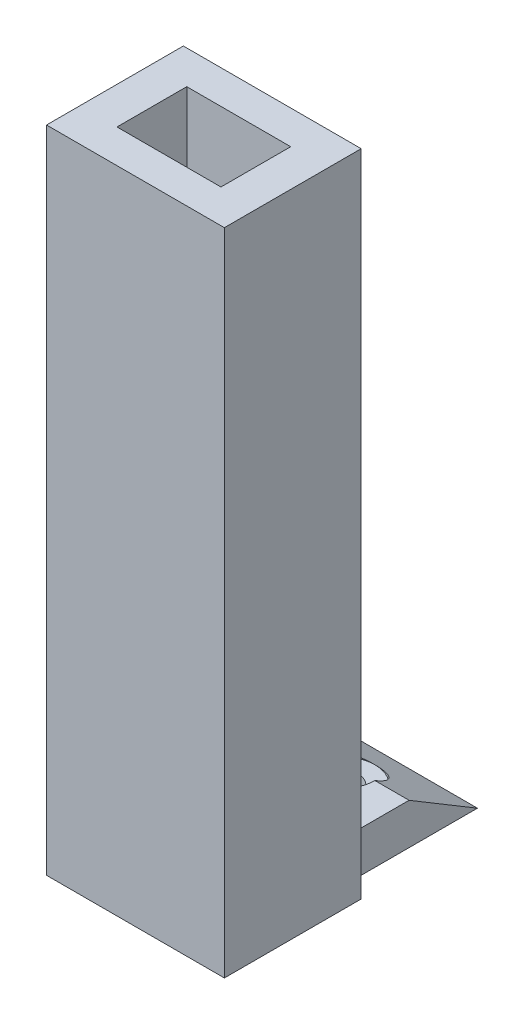
SolidWorks part; units mm, degrees
ref_plane "前视基准面" through (0, 0, 0) normal (0, 0, 1) x (1, 0, 0)
ref_plane "上视基准面" through (0, 0, 0) normal (0, 1, 0) x (1, 0, 0)
ref_plane "右视基准面" through (0, 0, 0) normal (1, 0, 0) x (0, 0, -1)
other "Configuration Table"
sketch "草图1" plane through (0, 0, 0) normal (0, 1, 0) x (1, 0, 0)
  line L5 (-10, -10) -> (10, -10)
  line L7 (-10, 10) -> (10, 10)
  line L9 (10, 10) -> (13, 10)
  line L11 (10, -10) -> (13, -10)
  line L12 (13, 10) -> (13, -10)
  line L13 (-10, 10) -> (-13, 10)
  line L15 (-10, -10) -> (-13, -10)
  line L16 (-13, 10) -> (-13, -10)
extrude "凸台-拉伸1" add sketch "草图1" along normal blind 6 contours L7 L9 L12 L11 L5 L15 L16 L13
sketch "草图2" plane through (0, 6, 0) normal (0, 1, 0) x (1, 0, 0)
  circle A0 centre (0, 0) radius 2.6
extrude "切除-拉伸1" cut sketch "草图2" against normal blind 6
sketch "草图3" plane through (0, 6, 0) normal (0, 1, 0) x (1, 0, 0)
  circle A0 centre (0, 0) radius 5
extrude "切除-拉伸2" cut sketch "草图3" against normal blind 3
sketch "草图4" plane through (0, 6, 0) normal (0, 1, 0) x (1, 0, 0)
  line L1 (-13, 10) -> (13, 10)
  line L2 (-13, 10) -> (-13, -10)
  line L3 (-13, -10) -> (13, -10)
  line L4 (13, 10) -> (13, -10)
  line L5 (-7.5, 5) -> (7.5, 5)
  line L6 (-7.5, 5) -> (-7.5, -5)
  line L7 (-7.5, -5) -> (7.5, -5)
  line L8 (7.5, 5) -> (7.5, -5)
extrude "凸台-拉伸2" add sketch "草图4" along normal blind 89 contours L2 L1 L4 L3 | L6 L5 L8 L7
sketch "草图5" plane through (0, 0, -10) normal (0, 0, -1) x (-1, 0, 0)
  line L0 (0, 0) -> (0, 6)
  line L3 (-7.5, 30) -> (-7.5, 50)
  line L9 (-7.5, 15) -> (-7.5, 30)
  line L11 (7.5, 15) -> (7.5, 30)
  line L12 (-7.5, 50) -> (7.5, 50)
  line L13 (7.5, 30) -> (7.5, 50)
  line L14 (13, 0) -> (-13, 0) construction
  line L16 (0, 6) -> (-7.5, 6)
  line L19 (-7.5, 6) -> (-7.5, 15)
  line L20 (0, 6) -> (7.5, 6)
  line L23 (7.5, 6) -> (7.5, 15)
extrude "切除-拉伸5" cut sketch "草图5" against normal blind 5 contours L20 L23 L11 L13 L12 L3 L9 L19 L16
sketch "草图6" plane through (0, 0, -10) normal (0, 0, -1) x (-1, 0, 0)
  line L0 (7.5, 6) -> (0, 6) construction
  line L1 (7.5, 50) -> (6.5, 50)
  line L2 (7.5, 50) -> (7.5, 6)
  line L3 (7.5, 6) -> (6.5, 6)
  line L4 (6.5, 50) -> (6.5, 6)
  line L5 (-7.5, 6) -> (7.5, 6) construction
  line L6 (-7.5, 50) -> (-6.5, 50)
  line L7 (-7.5, 50) -> (-7.5, 6)
  line L8 (-7.5, 6) -> (-6.5, 6)
  line L9 (-6.5, 50) -> (-6.5, 6)
extrude "凸台-拉伸3" add sketch "草图6" against normal blind 15
sketch "草图8" plane through (0, 0, 0) normal (0, -1, 0) x (1, 0, 0)
  line L1 (-13, -10) -> (13, -10)
  line L2 (-13, -10) -> (-13, -30)
  line L3 (-13, -30) -> (13, -30)
  line L4 (13, -10) -> (13, -30)
  circle A0 centre (0, -20) radius 2.6
extrude "凸台-拉伸4" add sketch "草图8" against normal blind 6
sketch "草图9" plane through (0, 6, 0) normal (0, 1, 0) x (1, 0, 0)
  circle A0 centre (0, 20) radius 5
extrude "切除-拉伸6" cut sketch "草图9" against normal blind 3
sketch "草图10" plane through (-13, 0, 0) normal (-1, 0, 0) x (0, 0, 1)
  line L0 (-20, 6) -> (-30, 0)
  line L1 (-10, 6) -> (-30, 6) construction
  line L2 (-30, 0) -> (-30, 6)
  line L3 (-30, 6) -> (-20, 6)
extrude "切除-拉伸7" cut sketch "草图10" against normal blind 30 contours L3 L0 L2
sketch "草图11" plane through (0, 0, -10) normal (0, 0, -1) x (-1, 0, 0)
  line L0 (13, 0) -> (-13, 0) construction
  line L1 (-13, 6) -> (-10, 6)
  line L2 (-13, 6) -> (-13, 0)
  line L3 (-13, 0) -> (-10, 0)
  line L4 (-10, 6) -> (-10, 0)
  line L6 (13, 6) -> (10, 6)
  line L7 (13, 6) -> (13, 0)
  line L8 (13, 0) -> (10, 0)
  line L9 (10, 6) -> (10, 0)
extrude "切除-拉伸8" cut sketch "草图11" along normal blind 30
sketch "草图12" plane through (0, 95, 0) normal (0, 1, 0) x (1, 0, 0)
  line L0 (-7.5, 5) -> (-7.5, 5.1)
  line L1 (-7.5, 5.1) -> (-7.6, 5.1)
  line L2 (7.5, -5) -> (7.6, -5)
  line L3 (7.6, -5) -> (7.6, -5.1)
  line L5 (7.6, -5.1) -> (-7.6, -5.1)
  line L6 (7.6, -5.1) -> (7.6, 5.1)
  line L7 (7.6, 5.1) -> (-7.6, 5.1)
  line L8 (-7.6, -5.1) -> (-7.6, 5.1)
  line M17 (7.5, -5) -> (-7.5, -5)
  line M18 (-7.5, -5) -> (-7.5, 5)
  line M19 (-7.5, 5) -> (7.5, 5)
  line M20 (7.5, 5) -> (7.5, -5)
extrude "切除-拉伸10" cut sketch "草图12" against normal blind 45 contours L6 L7 L0 L2 M19 M20 | L8 L5 L3 L2 L0 L1 M17 M18
